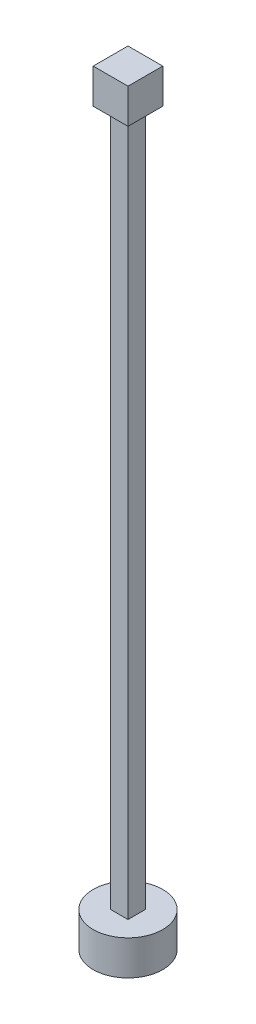
SolidWorks part; units mm, degrees
ref_plane "Front Plane" through (0, 0, 0) normal (0, 0, 1) x (1, 0, 0)
ref_plane "Top Plane" through (0, 0, 0) normal (0, 1, 0) x (1, 0, 0)
ref_plane "Right Plane" through (0, 0, 0) normal (1, 0, 0) x (0, 0, -1)
sketch "Sketch1" plane through (0, 0, 0) normal (0, 1, 0) x (1, 0, 0)
  circle A0 centre (0, 0) radius 50
  dimension "D1" = 100
extrude "Boss-Extrude1" add sketch "Sketch1" along normal blind 50
sketch "Sketch2" plane through (0, 50, 0) normal (0, 1, 0) x (1, 0, 0)
  line L1 (-12.5, 12.5) -> (12.5, 12.5)
  line L2 (-12.5, 12.5) -> (-12.5, -12.5)
  line L3 (-12.5, -12.5) -> (12.5, -12.5)
  line L4 (12.5, 12.5) -> (12.5, -12.5)
  line L5 (-12.5, 12.5) -> (12.5, -12.5) construction
  line L6 (-12.5, -12.5) -> (12.5, 12.5) construction
  point P0 (0, 0)
  dimension "D1" = 25
  dimension "D2" = 25
extrude "Boss-Extrude2" add sketch "Sketch2" along normal blind 1000
sketch "Sketch3" plane through (0, 1050, 0) normal (0, 1, 0) x (1, 0, 0)
  line L1 (-25, 25) -> (25, 25)
  line L2 (-25, 25) -> (-25, -25)
  line L3 (-25, -25) -> (25, -25)
  line L4 (25, 25) -> (25, -25)
  line L5 (-25, 25) -> (25, -25) construction
  line L6 (-25, -25) -> (25, 25) construction
  point P0 (0, 0)
  dimension "D1" = 50
  dimension "D2" = 50
extrude "Boss-Extrude3" add sketch "Sketch3" along normal blind 50
